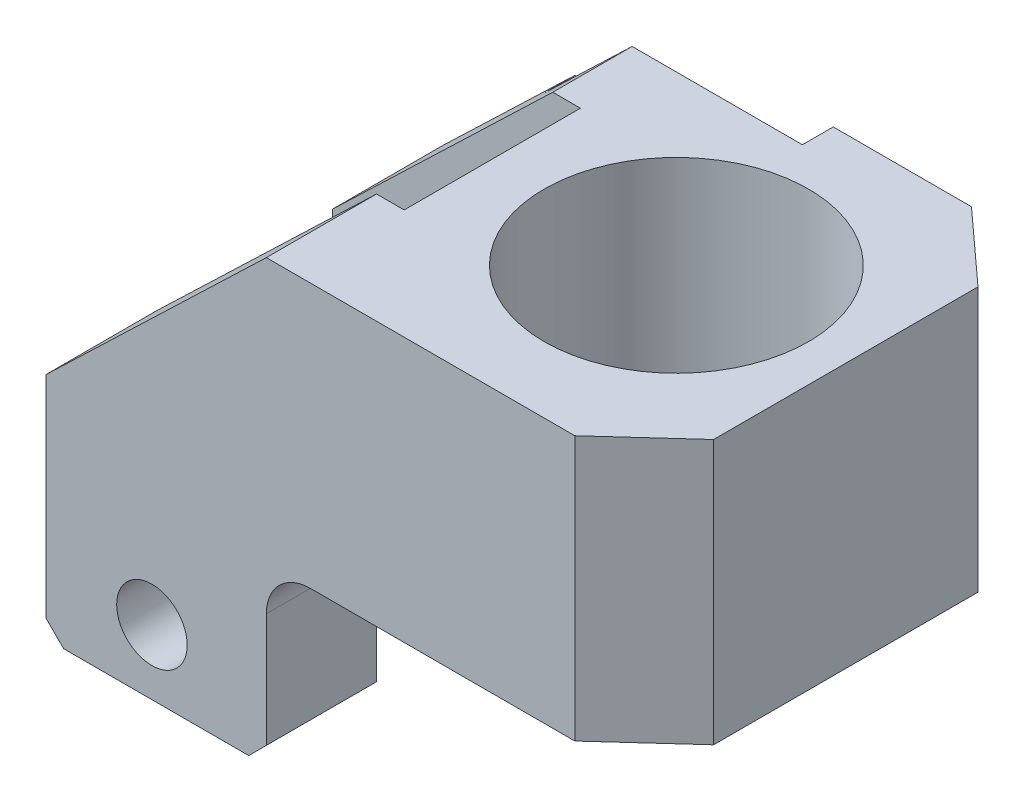
SolidWorks part; units mm, degrees
ref_plane "Спереди" through (0, 0, 0) normal (0, 0, 1) x (1, 0, 0)
ref_plane "Сверху" through (0, 0, 0) normal (0, 1, 0) x (1, 0, 0)
ref_plane "Справа" through (0, 0, 0) normal (1, 0, 0) x (0, 0, -1)
sketch "Эскиз1" plane through (0, 0, 0) normal (0, 1, 0) x (1, 0, 0)
  line L0 (-8.5273, 0) -> (45.8432, 0) construction
  line L1 (-24.0191, 22.5) -> (10.9809, 22.5)
  line L2 (-24.0191, 22.5) -> (-24.0191, -22.5)
  line L3 (-24.0191, -22.5) -> (10.9809, -22.5)
  line L4 (19.2235, 15) -> (19.2235, -15)
  line L7 (10.9809, -22.5) -> (19.2235, -15)
  line L8 (10.9809, 22.5) -> (19.2235, 15)
extrude "Вытянуть1" add sketch "Эскиз1" along normal blind 30
sketch "Эскиз2" plane through (0, 30, 0) normal (0, 1, 0) x (1, 0, 0)
  circle A0 centre (0, 0) radius 15
extrude "Вытянуть2" cut sketch "Эскиз2" against normal through all
sketch "Эскиз6" plane through (0, 0, -22.5) normal (0, 0, -1) x (-1, 0, 0)
  line L0 (24.0191, -19.9275) -> (24.0191, 30)
  line L2 (49.0191, -19.9275) -> (49.0191, 6.0126)
  line L3 (49.0191, -19.9275) -> (24.0191, -19.9275)
  line L4 (24.0191, 30) -> (49.0191, 6.0126)
extrude "Вытянуть3" add sketch "Эскиз6" against normal up to vertex (45 mm away) up to point (-24.0191, 30, 22.5)
sketch "Эскиз3" plane through (0, 30, 0) normal (0, 1, 0) x (1, 0, 0)
  line L0 (-38.6818, 0) -> (-47.6939, 0) construction
  line L3 (-65.5391, 10) -> (-20.8824, 10)
  line L4 (-65.5391, 10) -> (-65.5391, -10)
  line L5 (-65.5391, -10) -> (-20.8824, -10)
  line L6 (-20.8824, 10) -> (-20.8824, -10)
  line L7 (-65.5391, 10) -> (-20.8824, -10) construction
  line L8 (-65.5391, -10) -> (-20.8824, 10) construction
  point P1 (-43.2108, 0)
extrude "Вырез-Вытянуть1" cut sketch "Эскиз3" against normal blind 130 from offset 70
sketch "Эскиз7" plane through (0, 0, -22.5) normal (0, 0, -1) x (-1, 0, 0)
  circle A0 centre (37, -12.5783) radius 4
extrude "Вырез-Вытянуть2" cut sketch "Эскиз7" against normal through all
fillet "Скругление1" radius 5 1 edges
chamfer "Фаска5" distance 2 angle 45 4 edges at (-24.0191, -19.9275, -16.25) (-24.0191, -19.9275, 16.25) (-49.0191, -19.9275, -16.25) (-49.0191, -19.9275, 16.25)
sketch "Эскиз10" plane through (0, 0, -22.5) normal (0, 0, -1) x (-1, 0, 0)
  circle A0 centre (21.576, 32.0594) radius 17
extrude "Вырез-Вытянуть5" cut sketch "Эскиз10" against normal blind 3.5
